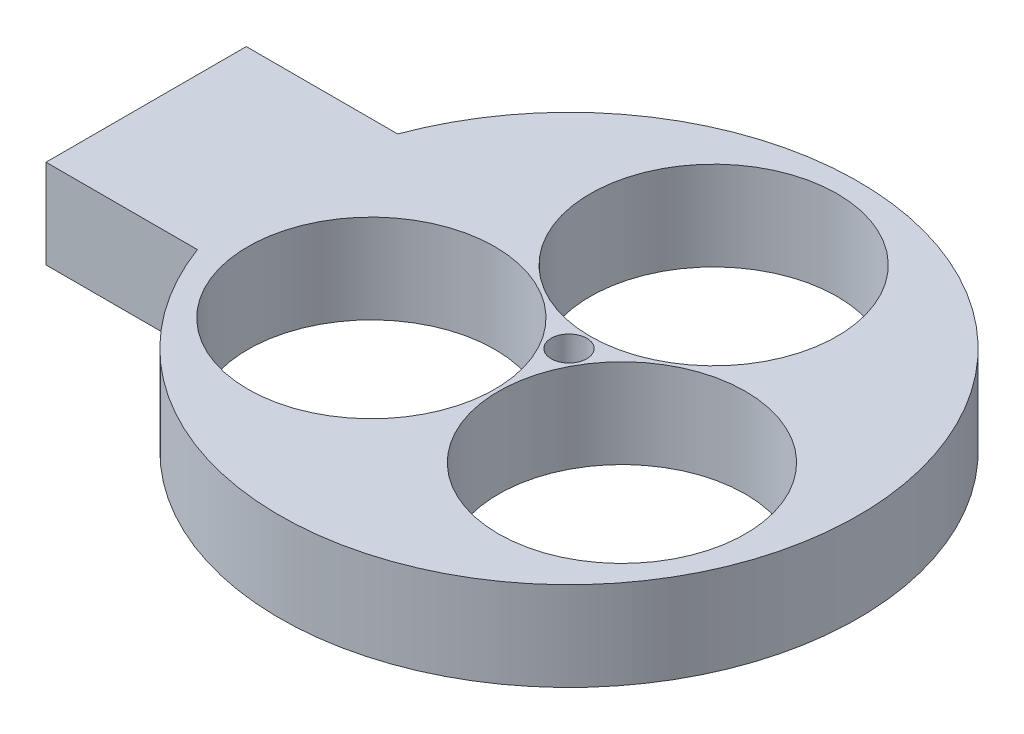
SolidWorks part; units mm, degrees
material "Nylon 101"
ref_plane "Alzado" through (0, 0, 0) normal (0, 0, 1) x (1, 0, 0)
ref_plane "Planta" through (0, 0, 0) normal (0, 1, 0) x (1, 0, 0)
ref_plane "Vista lateral" through (0, 0, 0) normal (1, 0, 0) x (0, 0, -1)
ref_plane "Plane2" through (0, -2, 0) normal (0, 1, 0) x (1, 0, 0)
sketch "Sketch1" plane through (0, -2, 0) normal (0, 1, 0) x (1, 0, 0)
  circle A0 centre (0, 0) radius 13.0007
  circle A1 centre (0, 6.5) radius 5.55
  circle A2 centre (-5.63, -3.25) radius 5.55
  circle A3 centre (5.63, -3.25) radius 5.55
  circle A4 centre (0, 0) radius 0.8
extrude "Placa_cabezal" add sketch "Sketch1" along normal blind 4
sketch "Sketch2" plane through (0, -2, 0) normal (0, 1, 0) x (1, 0, 0)
  line L0 (-19.0007, -4.5) -> (-11.5007, -4.5)
  line L1 (-11.5007, -4.5) -> (-11.5007, 4.5)
  line L2 (-11.5007, 4.5) -> (-19.0007, 4.5)
  line L3 (-19.0007, 4.5) -> (-19.0007, -4.5)
extrude "Pata_al_hueso" add sketch "Sketch2" along normal blind 4
